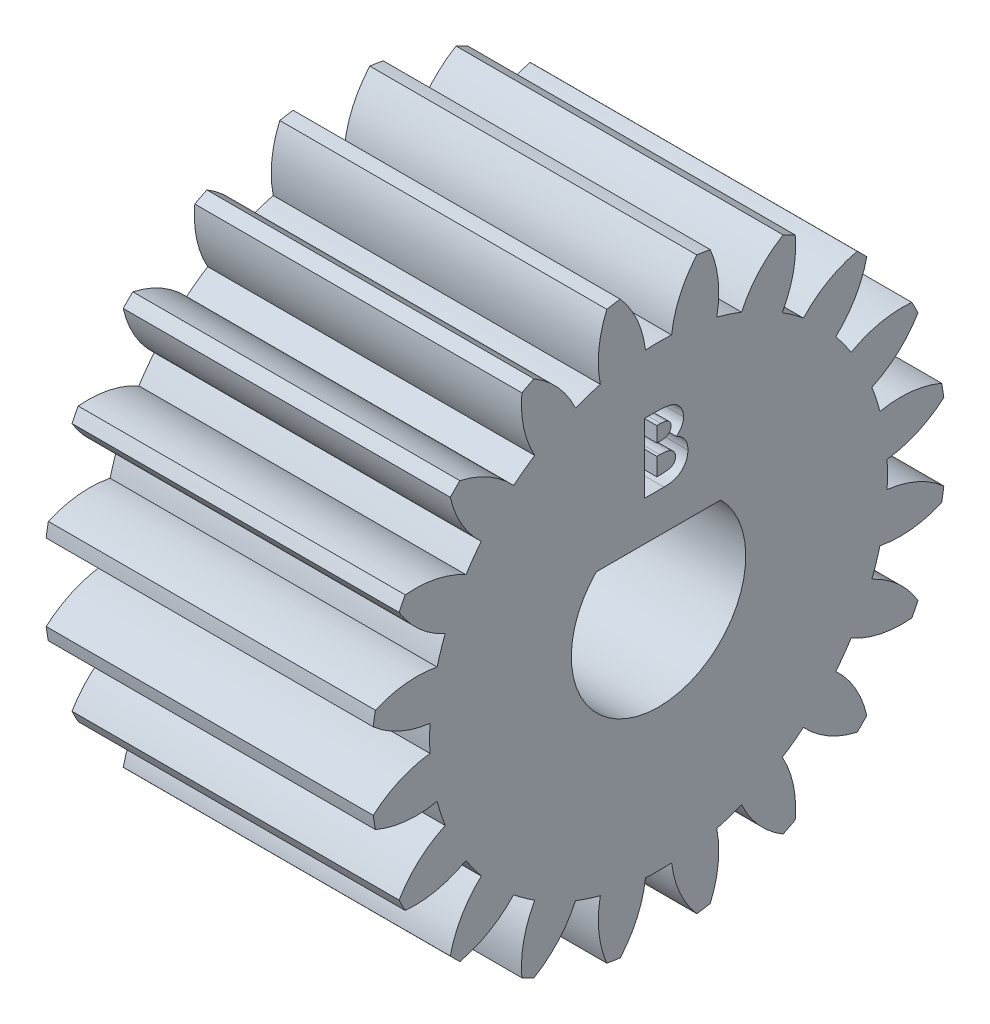
SolidWorks part; units mm, degrees
ref_plane "Plane1" through (0, 0, 0) normal (0, 0, 1) x (1, 0, 0)
ref_plane "Plane2" through (0, 0, 0) normal (0, 1, 0) x (1, 0, 0)
ref_plane "Plane3" through (0, 0, 0) normal (1, 0, 0) x (0, 0, -1)
sketch "HoldingSke" plane through (0, 0, 0) normal (0, 1, 0) x (1, 0, 0)
  line L0 (0, 0) -> (0.7831, -0.285)
  line L1 (-15, 0) -> (100, 0) construction
  line L2 (0, 0) -> (-2.1039, 2.3779)
  line L3 (0, 0) -> (-11.863, 4.5341)
  line L4 (0, 0) -> (8.1152, 2.9537)
  line L5 (0, 0) -> (-46.8476, -17.4728)
  line L6 (0, 0) -> (-12.4344, -8.3896)
  line L7 (-2.1039, 2.3779) -> (8.6586, 51.2059)
  line L8 (-76.2, 54.61) -> (-74.8, 54.61)
  line L9 (-71.009, 38.7566) -> (-53.1078, 45.2721)
  line L10 (-76.2, 71.12) -> (104.1128, 71.12)
  line L11 (0, 0) -> (-15, 0)
  line L12 (-76.2, 101.6) -> (-76.155, 101.6)
  line L13 (24.9733, 27.94) -> (52.9518, 28.4284)
  line L14 (24.9733, 27.94) -> (24.9743, 27.94)
  line L15 (24.9733, 27.94) -> (100.4006, 29.5858)
  line L16 (-63.627, -1.2) -> (-12.827, -1.2)
  circle A0 centre (0, 0) radius 4
  circle A1 centre (0, 0) radius 10.499
  circle A2 centre (0, 0) radius 37.5
  circle A3 centre (0, 0) radius 4
  dimension "MHD" = 20.998
  dimension "Hub_dia" = 75
  dimension "Bore" = 8
  dimension "MBD" = 8
  dimension "Num_teeth" = 20
  dimension "Pitch" = 0.8333
  dimension "Overall_len" = 50
  dimension "Show_teeth" = 20
  dimension "Thickness" = 15
  dimension "OAL" = 50.0001
  dimension "T_dim" = 1.4
  dimension "Ap" = 20
  dimension "H" = 19.05
  dimension "Pitch_radius" = 180.3128
  dimension "Width" = 15
  dimension "Backlash" = 0.045
  dimension "Addendum_fac" = 1
  dimension "Dedendum_fac" = 1.25
  dimension "Clearance_fac" = 0.25
  dimension "Dedendum_add" = 0.001
  dimension "Module" = 1.2
sketch "BasProSke" plane through (0, 0, 0) normal (0, 1, 0) x (1, 0, 0)
  line L0 (-10, 0) -> (60, 0) construction
  line L1 (0, 0) -> (0, 13.2)
  line L2 (0, 0) -> (15, 0)
  line L3 (15, 0) -> (15, 13.2)
  line L4 (15, 13.2) -> (0, 13.2)
  dimension "Thickness" = 15
  dimension "Diameter" = 26.4
revolve "Base-Revolve" add sketch "BasProSke" angle 360 about L0
sketch "TooCutSke" plane through (0, 0, 0) normal (1, 0, 0) x (0, 0, -1)
  line L1 (0, 0) -> (0, 107) construction
  line L2 (0, 0) -> (-1.0202, 11.9566) construction
  line L3 (0, 0) -> (-3.7447, 23.6432) construction
  line L4 (-1.0202, 11.9566) -> (-1.8724, 11.8216) construction
  arc A0 (0.599, 10.4819) -> (-0.599, 10.4819) centre (0, 0) ccw
  arc A1 (1.777, 13.1055) -> (-1.777, 13.1055) centre (0, 0) ccw
  circle A2 centre (0, 0) radius 12 construction
  circle A3 centre (0, 0) radius 11.2763 construction
  arc A4 (-0.599, 10.4819) -> (-1.777, 13.1055) centre (-5.3658, 9.9179) ccw
  arc A5 (1.777, 13.1055) -> (0.599, 10.4819) centre (5.3658, 9.9179) ccw
  dimension "Root_dia" = 20.998
  dimension "Overcut_dia" = 26.4508
  dimension "Pitch_dia" = 24
  dimension "Base_dia" = 22.5526
  dimension "Flank_rad" = 4.8
  dimension "Half_ang" = 9
  dimension "Half_CT" = 0.8628
extrude "ToothCut" cut sketch "TooCutSke" along normal through all
fillet "Breaks" [suppressed] radius 0.024
fillet "RootFillets" [suppressed] radius 0.301
pattern_circular "TeethCuts" count 20 every 18 about axis through (-10, 0, 0) along (1, 0, 0) of "ToothCut", "RootFillets", "Breaks"
sketch "HubNeaOneSke" plane through (0, 0, 0) normal (-1, 0, 0) x (0, 0, 1)
  circle A0 centre (0, 0) radius 10.499
  dimension "Diameter" = 20.998
extrude "HubNearOne" [suppressed] add sketch "HubNeaOneSke" along normal blind 35.0001
sketch "HubNeaBotSke" plane through (0, 0, 0) normal (-1, 0, 0) x (0, 0, 1)
  circle A0 centre (0, 0) radius 10.499
  dimension "Diameter" = 20.998
extrude "HubNearBoth" [suppressed] add sketch "HubNeaBotSke" along normal blind 17.5
ref_plane "FarPln" through (15, 0, 0) normal (1, 0, 0) x (0, 0, -1)
sketch "HubFarSke" plane through (15, 0, 0) normal (1, 0, 0) x (0, 0, -1)
  circle A0 centre (0, 0) radius 10.499
  dimension "Diameter" = 20.998
extrude "HubFar" [suppressed] add sketch "HubFarSke" along normal blind 17.5
sketch "BorSke" plane through (0, 0, 0) normal (1, 0, 0) x (0, 0, -1)
  circle A0 centre (0, 0) radius 4
  dimension "Diameter" = 8
extrude "Bore" cut sketch "BorSke" along normal mid plane 100.0001
sketch "KeySke" plane through (0, 0, 0) normal (1, 0, 0) x (0, 0, -1)
  line L0 (-1.5, 0) -> (-1.5, 5.4)
  line L1 (-1.5, 5.4) -> (1.5, 5.4)
  line L2 (1.5, 5.4) -> (1.5, 0)
  line L3 (0, 0) -> (0, 34) construction
  line L4 (-1.5, 0) -> (1.5, 0)
  dimension "Offset" = 5.4
  dimension "Width" = 3
extrude "Keyway" [suppressed] cut sketch "KeySke" along normal mid plane 100.0001
pattern_circular "Keyway2" [suppressed] count 2 every 90 about axis through (-10, 0, 0) along (1, 0, 0)
sketch "Sketch1" plane through (0, 0, 0) normal (-1, 0, 0) x (0, 0, 1)
  line L0 (0, 0) -> (0, 8) construction
  line L1 (0, 0) -> (0, 2.8) construction
  line L2 (0, 2.8) -> (0, 4) construction
  line L3 (2.8566, 2.8) -> (-2.8566, 2.8)
  circle A0 centre (0, 0) radius 4 construction
  circle A1 centre (0, 0) radius 8 construction
  circle A2 centre (0, 0) radius 4 construction
  arc A3 (2.8566, 2.8) -> (-2.8566, 2.8) centre (0, 0) ccw
  point P12 (0, 2.8)
  dimension "D1" = 16
  dimension "D2" = 1.2
  dimension "D3" = 0
extrude "Boss-Extrude1" add sketch "Sketch1" against normal up to surface (15 mm away) up to face at (15, 0, 4)
sketch "Sketch2" plane through (0, 0, 0) normal (-1, 0, 0) x (0, 0, 1)
  circle A0 centre (0, 0) radius 6
  circle A1 centre (0, 0) radius 7.2
  dimension "D1" = 12
  dimension "D2" = 14.4
extrude "Cut-Extrude1" cut sketch "Sketch2" against normal blind 0.5
sketch "Sketch3" plane through (15, 0, 0) normal (1, 0, 0) x (0, 0, -1)
  text T0 "B" font "Century Gothic" height in points 12
extrude "Cut-Extrude2" cut sketch "Sketch3" against normal blind 2
equation "' \"Module@HoldingSke\" = 6.35"
equation "' \"Num_teeth@HoldingSke\" = 12"
equation "' \"Ap@HoldingSke\" =  20"
equation "' \"Ap@HoldingSke\" = 20"
equation "' \"Width@HoldingSke\" = 0.5 * 25.4"
equation "' \"Hub_dia@HoldingSke\"= 1 * 25.4"
equation "' \"Hub_dia@HoldingSke\" = 1 * 25.4"
equation "' \"Overall_len@HoldingSke\" = 1.0 * 25.4"
equation "' \"Bore@HoldingSke\" = 0.75 * 25.4"
equation "' \"T_dim@HoldingSke\" = 0.1 * 25.4"
equation "' \"Width@KeySke\" = 0.25 * 25.4"
equation "' \"Show_teeth@HoldingSke\" = 13"
equation "' \"Backlash@HoldingSke\" = 0.009 * 25.4"
equation "' \"Addendum_fac@HoldingSke\" = 1.0"
equation "' \"Dedendum_fac@HoldingSke\" = 1.25"
equation "' \"Dedendum_add@HoldingSke\" = 0.00005 * 25.4"
equation "' \"Clearance_fac@HoldingSke\" = 0.25"
equation "\"Pitch@HoldingSke\" = 1 / \"Module@HoldingSke\""
equation "\"Overcut_dia@TooCutSke\" = (\"Num_teeth@HoldingSke\" + 2 * \"Addendum_fac@HoldingSke\") / \"Pitch@HoldingSke\" + 0.002 * 25.4"
equation "\"Pitch_dia@TooCutSke\" = \"Num_teeth@HoldingSke\" / \"Pitch@HoldingSke\""
equation "\"Base_dia@TooCutSke\" = \"Num_teeth@HoldingSke\" / \"Pitch@HoldingSke\" * cos((\"Ap@HoldingSke\"  * 3.14159265 / 180))"
equation "\"Root_dia@TooCutSke\" = (\"Num_teeth@HoldingSke\" + 2) / \"Pitch@HoldingSke\" - 2 * (\"Addendum_fac@HoldingSke\" + \"Dedendum_fac@HoldingSke\") / \"Pitch@HoldingSke\" - \"Dedendum_add@HoldingSke\" * 2"
equation "\"Half_ang@TooCutSke\" = 180 / \"Num_teeth@HoldingSke\""
equation "\"Half_CT@TooCutSke\" = \"Num_teeth@HoldingSke\" / \"Pitch@HoldingSke\" * sin((3.14159265 / 2 / \"Num_teeth@HoldingSke\")) / 2 - 7 * \"Backlash@HoldingSke\" / 4"
equation "\"Flank_rad@TooCutSke\" = \"Num_teeth@HoldingSke\" / \"Pitch@HoldingSke\" / 5"
equation "\"Radius@RootFillets\" = \"Clearance_fac@HoldingSke\" / \"Pitch@HoldingSke\" + \"Dedendum_add@HoldingSke\""
equation "\"Break_rad@Breaks\" = 0.02 / \"Pitch@HoldingSke\""
equation "\"Thickness@HoldingSke\" = \"Width@HoldingSke\""
equation "\"OAL@HoldingSke\" = \"Thickness@HoldingSke\""
equation "\"MHD@HoldingSke\" = (\"Num_teeth@HoldingSke\" + 2) / \"Pitch@HoldingSke\" - 2 * (\"Addendum_fac@HoldingSke\" + \"Dedendum_fac@HoldingSke\")  / \"Pitch@HoldingSke\" - \"Dedendum_add@HoldingSke\" * 2"
equation "\"MBD@HoldingSke\" = (\"Num_teeth@HoldingSke\" + 2) / \"Pitch@HoldingSke\" - 2 * (\"Addendum_fac@HoldingSke\" + \"Dedendum_fac@HoldingSke\")  / \"Pitch@HoldingSke\" - \"Dedendum_add@HoldingSke\" * 2 - 0.002 * 25.4"
equation "\"MHD@HoldingSke\" = ((sgn( \"MHD@HoldingSke\" - \"Hub_dia@HoldingSke\" )-1)*( \"MHD@HoldingSke\" - \"Hub_dia@HoldingSke\" ))/-2+ \"Hub_dia@HoldingSke\""
equation "\"MBD@HoldingSke\" = ((sgn( \"MBD@HoldingSke\" - \"Bore@HoldingSke\" )-1)*( \"MBD@HoldingSke\" - \"Bore@HoldingSke\" ))/-2+ \"Bore@HoldingSke\""
equation "\"OAL@HoldingSke\" = ((sgn( \"OAL@HoldingSke\" - \"Overall_len@HoldingSke\" )+1)*( \"OAL@HoldingSke\" - \"Overall_len@HoldingSke\" ))/2 + \"Overall_len@HoldingSke\" + 0.000002 * 25.4"
equation "\"Num_teeth@TeethCuts\" = int( \"Show_teeth@HoldingSke\" ) + 1"
equation "\"Num_teeth@TeethCuts\" = ((sgn( \"Num_teeth@TeethCuts\" - \"Num_teeth@HoldingSke\" )-1)*( \"Num_teeth@TeethCuts\" - \"Num_teeth@HoldingSke\" ))/-2+ \"Num_teeth@HoldingSke\""
equation "\"Num_teeth@TeethCuts\" = ((sgn( \"Num_teeth@TeethCuts\" - 2.0)+1)*( \"Num_teeth@TeethCuts\" - 2.0))/2 +2.0"
equation "\"Angle@TeethCuts\" = 360.0 / \"Num_teeth@HoldingSke\""
equation "\"Diameter@BasProSke\" = (\"Num_teeth@HoldingSke\" + 2 * \"Addendum_fac@HoldingSke\") / \"Pitch@HoldingSke\""
equation "\"Thickness@BasProSke\"  = \"Thickness@HoldingSke\""
equation "' \"Fillet_rad@BasProSke\" =  \"Thickness@HoldingSke\" * 0.05"
equation "' \"Fillet_rad@BasProSke\" = \"Thickness@HoldingSke\" * 0.05"
equation "\"MHD@HoldingSke\" = ((sgn( \"MHD@HoldingSke\" - \"Root_dia@TooCutSke\" )-1)*( \"MHD@HoldingSke\" - \"Root_dia@TooCutSke\" ))/-2+ \"Root_dia@TooCutSke\""
equation "\"Diameter@HubNeaOneSke\" = \"MHD@HoldingSke\""
equation "\"Length@HubNearOne\" = \"OAL@HoldingSke\" - \"Thickness@BasProSke\""
equation "\"Diameter@HubNeaBotSke\" = \"MHD@HoldingSke\""
equation "\"Length@HubNearBoth\" = ( \"OAL@HoldingSke\" - \"Thickness@BasProSke\" ) / 2.0"
equation "\"Thickness@FarPln\" = \"Thickness@BasProSke\""
equation "\"Diameter@HubFarSke\" = \"MHD@HoldingSke\""
equation "\"Length@HubFar\" = ( \"OAL@HoldingSke\" - \"Thickness@BasProSke\" ) / 2.0"
equation "\"Diameter@BorSke\" = \"MBD@HoldingSke\""
equation "\"D1@Bore\" = \"OAL@HoldingSke\" * 2.0"
equation "\"D1@Keyway\" = \"OAL@HoldingSke\" * 2.0"
equation "\"Offset@KeySke\" = \"T_dim@HoldingSke\" + \"MBD@HoldingSke\" / 2.0"
